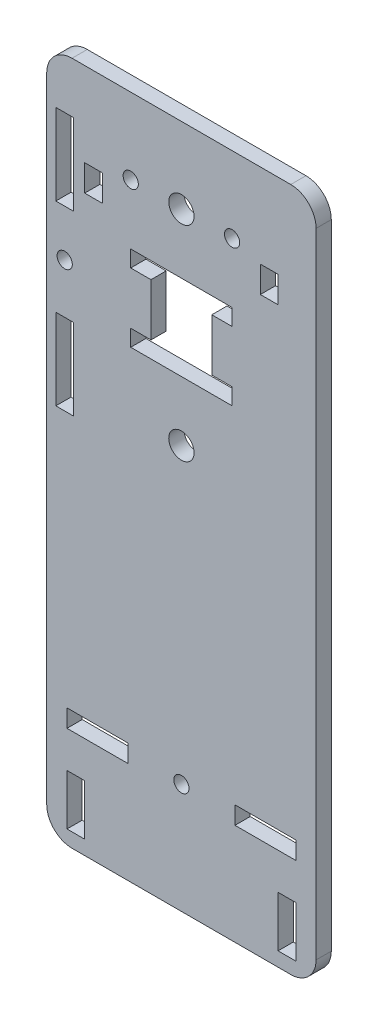
SolidWorks part; units mm, degrees
ref_plane "Alzado" through (0, 0, 0) normal (0, 0, 1) x (1, 0, 0)
ref_plane "Planta" through (0, 0, 0) normal (0, 1, 0) x (1, 0, 0)
ref_plane "Vista lateral" through (0, 0, 0) normal (1, 0, 0) x (0, 0, -1)
sketch "Croquis1" plane through (0, 0, 0) normal (0, 0, 1) x (1, 0, 0)
  line L0 (0, -67.5) -> (0, 67.5) construction
  line L1 (21.575, -67.5) -> (-21.575, -67.5)
  line L2 (26.575, -62.5) -> (26.575, 62.5)
  line L3 (21.575, 67.5) -> (-21.575, 67.5)
  line L4 (-26.575, -62.5) -> (-26.575, 62.5)
  line L5 (26.575, -67.5) -> (-26.575, 67.5) construction
  line L6 (26.575, 67.5) -> (-26.575, -67.5) construction
  line L7 (-26.575, 0) -> (26.575, 0) construction
  line L8 (-10.575, -44) -> (-22.575, -44)
  line L9 (22.575, -64.7) -> (19.075, -64.7)
  line L10 (22.575, -64.7) -> (22.575, -54.7)
  line L11 (22.575, -54.7) -> (19.075, -54.7)
  line L12 (19.075, -64.7) -> (19.075, -54.7)
  line L13 (22.575, -64.7) -> (19.075, -54.7) construction
  line L14 (22.575, -54.7) -> (19.075, -64.7) construction
  line L15 (10.575, -47.5) -> (22.575, -47.5)
  line L16 (10.575, -47.5) -> (10.575, -44)
  line L17 (10.575, -44) -> (22.575, -44)
  line L18 (22.575, -47.5) -> (22.575, -44)
  line L19 (10.575, -47.5) -> (22.575, -44) construction
  line L20 (10.575, -44) -> (22.575, -47.5) construction
  line L21 (-22.575, -47.5) -> (-22.575, -44)
  line L22 (-10.575, -47.5) -> (-22.575, -47.5)
  line L23 (-10.575, -47.5) -> (-10.575, -44)
  line L24 (-22.575, -54.7) -> (-19.075, -54.7)
  line L25 (-19.075, -64.7) -> (-19.075, -54.7)
  line L26 (-22.575, -64.7) -> (-19.075, -64.7)
  line L27 (-22.575, -64.7) -> (-22.575, -54.7)
  line L28 (10, 23.9) -> (-10, 23.9)
  line L29 (-24.775, 57.5) -> (-21.275, 57.5)
  line L30 (-24.775, 57.5) -> (-24.775, 41.5)
  line L31 (-24.775, 41.5) -> (-21.275, 41.5)
  line L32 (-21.275, 57.5) -> (-21.275, 41.5)
  line L33 (-24.775, 57.5) -> (-21.275, 41.5) construction
  line L34 (-24.775, 41.5) -> (-21.275, 57.5) construction
  line L35 (-24.775, 22.5) -> (-21.275, 22.5)
  line L36 (-24.775, 22.5) -> (-24.775, 6.5)
  line L37 (-24.775, 6.5) -> (-21.275, 6.5)
  line L38 (-21.275, 22.5) -> (-21.275, 6.5)
  line L39 (-24.775, 22.5) -> (-21.275, 6.5) construction
  line L40 (-24.775, 6.5) -> (-21.275, 22.5) construction
  line L41 (-10, 23.9) -> (-10, 27.15)
  line L42 (-10, 27.15) -> (-6, 27.15)
  line L43 (-6, 27.15) -> (-6, 37.45)
  line L44 (-6, 37.45) -> (-10, 37.45)
  line L45 (-10, 37.45) -> (-10, 40.7)
  line L46 (-10, 40.7) -> (10, 40.7)
  line L47 (10, 37.45) -> (10, 40.7)
  line L48 (6, 37.45) -> (10, 37.45)
  line L49 (6, 27.15) -> (6, 37.45)
  line L50 (10, 27.15) -> (6, 27.15)
  line L51 (10, 23.9) -> (10, 27.15)
  line L52 (-6, 32.3) -> (-26.575, 32.3) construction
  line L53 (19.075, 50.9) -> (15.575, 50.9)
  line L54 (-19.075, 45.7) -> (-15.575, 45.7)
  line L55 (-19.075, 45.7) -> (-19.075, 50.9)
  line L56 (-19.075, 50.9) -> (-15.575, 50.9)
  line L57 (-15.575, 45.7) -> (-15.575, 50.9)
  line L58 (-19.075, 45.7) -> (-15.575, 50.9) construction
  line L59 (-19.075, 50.9) -> (-15.575, 45.7) construction
  line L60 (15.575, 45.7) -> (15.575, 50.9)
  line L61 (19.075, 45.7) -> (15.575, 45.7)
  line L62 (19.075, 45.7) -> (19.075, 50.9)
  circle A0 centre (0, -45.75) radius 1.5
  arc A1 (21.575, -67.5) -> (26.575, -62.5) centre (21.575, -62.5) ccw
  arc A2 (-21.575, -67.5) -> (-26.575, -62.5) centre (-21.575, -62.5) cw
  arc A3 (26.575, 62.5) -> (21.575, 67.5) centre (21.575, 62.5) ccw
  arc A4 (-21.575, 67.5) -> (-26.575, 62.5) centre (-21.575, 62.5) ccw
  circle A5 centre (-23.025, 32.3) radius 1.5
  circle A7 centre (0, 52.5) radius 2.5
  circle A8 centre (-10, 52.5) radius 1.5
  circle A9 centre (10, 52.5) radius 1.5
  circle A10 centre (0, 12.1) radius 2.5
  point P0 (0, 0)
  point P10 (20.825, -59.7)
  point P15 (-23.025, 14.5)
  point P16 (16.575, -45.75)
  point P21 (10.575, -45.75)
  point P44 (-23.025, 49.5)
  point P63 (0, 40.7)
  point P68 (0, 23.9)
  point P71 (-17.325, 48.3)
  point P76 (-17.325, 50.9)
  dimension "D10" = 3
  dimension "D11" = 5
  dimension "D22" = 3
  dimension "D27" = 5
  dimension "D29" = 3
  dimension "D1" = 53.15
  dimension "D2" = 135
  dimension "D3" = 2.8
  dimension "D4" = 4
  dimension "D5" = 3.5
  dimension "D6" = 10
  dimension "D7" = 4
  dimension "D8" = 20
  dimension "D9" = 12
  dimension "D12" = 1.8
  dimension "D13" = 16
  dimension "D14" = 10
  dimension "D15" = 3.5
  dimension "D16" = 45
  dimension "D17" = 26.8
  dimension "D18" = 10
  dimension "D19" = 3.25
  dimension "D20" = 16.8
  dimension "D21" = 6
  dimension "D23" = 16.6
  dimension "D24" = 5.2
  dimension "D25" = 3.5
  dimension "D26" = 7.5
  dimension "D28" = 15
  dimension "D30" = 10
extrude "Saliente-Extruir1" add sketch "Croquis1" along normal blind 3
